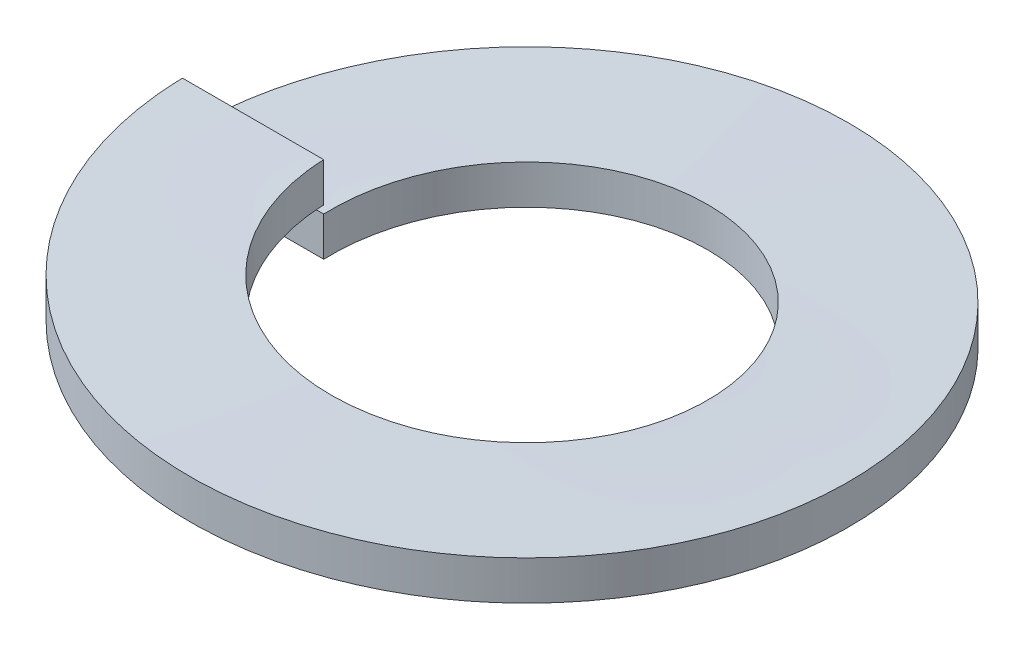
SolidWorks part; units mm, degrees
material "AISI 1020"
ref_plane "Front Plane" through (0, 0, 0) normal (0, 0, 1) x (1, 0, 0)
ref_plane "Top Plane" through (0, 0, 0) normal (0, 1, 0) x (1, 0, 0)
ref_plane "Right Plane" through (0, 0, 0) normal (1, 0, 0) x (0, 0, -1)
sketch "Sketch2" plane through (0, 0, 0) normal (0, 1, 0) x (1, 0, 0)
  circle A0 centre (0, 0) radius 10.5
  dimension "D1" = 21
curve "Helix/Spiral1" pitch 1.5 height 1.5 turns 1
sketch "Sketch3" plane through (0, 0, 0) normal (0, 0, 1) x (1, 0, 0)
  line L1 (-10.5, 0) -> (-6, 0)
  line L2 (-10.5, 0) -> (-10.5, 1.25)
  line L3 (-10.5, 1.25) -> (-6, 1.25)
  line L4 (-6, 0) -> (-6, 1.25)
  spline S0 degree 3 poles (-10.5, 0) (-10.5, 0.031) (-9.9533, 0.0938) (-7.6179, 0.1875) (-4.1228, 0.2813) (0, 0.375) (4.1228, 0.4688) (7.6179, 0.5625) (9.9533, 0.6563) (10.7734, 0.75) (9.9533, 0.8437) (7.6179, 0.9375) (4.1228, 1.0312) (0, 1.125) (-4.1228, 1.2187) (-7.6179, 1.3125) (-9.9533, 1.4062) (-10.5, 1.469) (-10.5, 1.5) knots 0 0 0 0 0.0625 0.125 0.1875 0.25 0.3125 0.375 0.4375 0.5 0.5625 0.625 0.6875 0.75 0.8125 0.875 0.9375 1 1 1 1 construction
  dimension "D1" = 1.25
  dimension "D2" = 4.5
sweep "Sweep1" add profiles "Sketch3" path "Helix/Spiral1"
sketch "Sketch4" plane through (0, 0, 0) normal (1, 0, 0) x (0, 0, -1)
  line L0 (0, 0) -> (0, 2.75) construction
